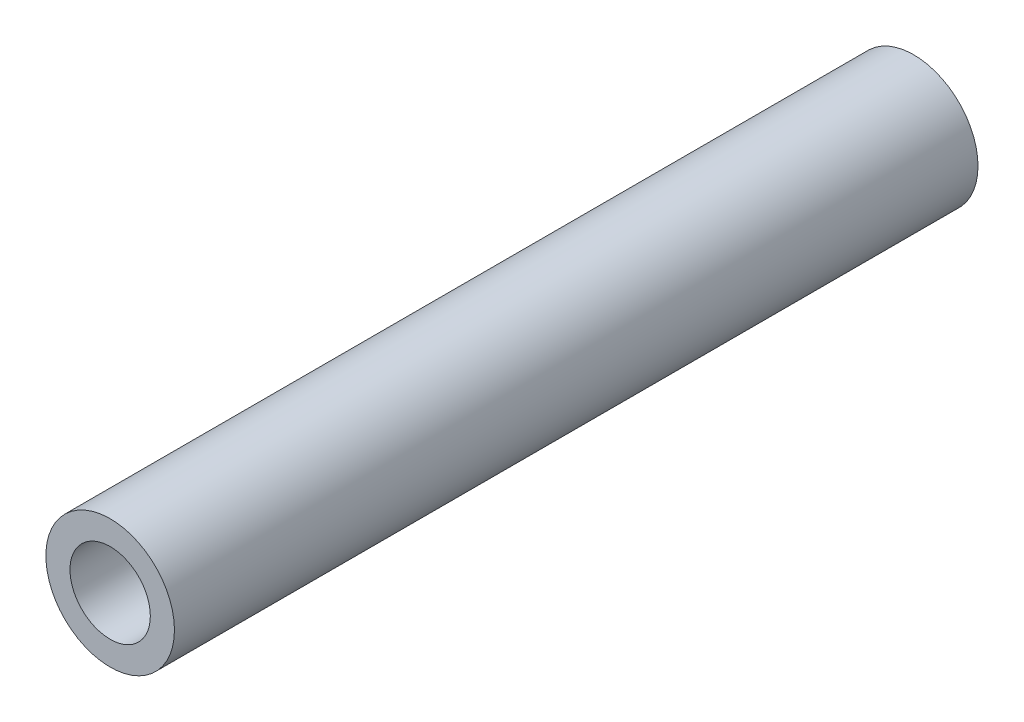
SolidWorks part; units mm, degrees
material "2.1016 (CuSn4)"
ref_plane "前视基准面" through (0, 0, 0) normal (0, 0, 1) x (1, 0, 0)
ref_plane "上视基准面" through (0, 0, 0) normal (0, 1, 0) x (1, 0, 0)
ref_plane "右视基准面" through (0, 0, 0) normal (1, 0, 0) x (0, 0, -1)
other "Configuration Table"
sketch "草图1" plane through (0, 0, 0) normal (0, 0, 1) x (1, 0, 0)
  circle A0 centre (0, 0) radius 2
  circle A1 centre (0, 0) radius 1.25
  dimension "D1" = 4
  dimension "D2" = 2.5
extrude "凸台-拉伸1" add sketch "草图1" along normal blind 25
